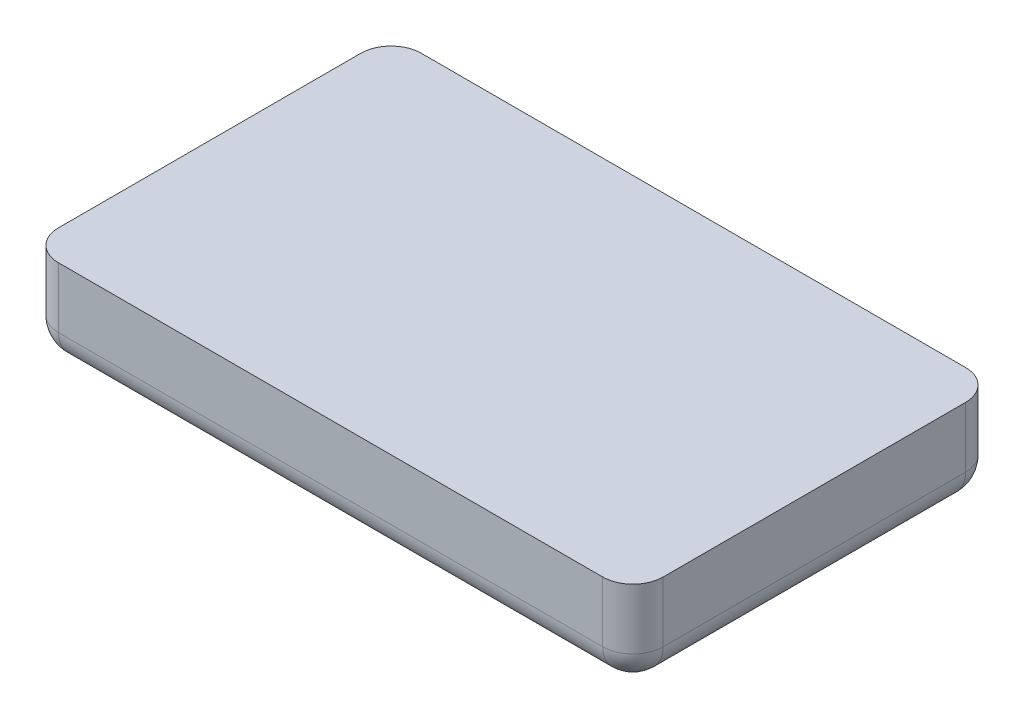
SolidWorks part; units mm, degrees
ref_plane "Front Plane" through (0, 0, 0) normal (0, 0, 1) x (1, 0, 0)
ref_plane "Top Plane" through (0, 0, 0) normal (0, 1, 0) x (1, 0, 0)
ref_plane "Right Plane" through (0, 0, 0) normal (1, 0, 0) x (0, 0, -1)
sketch "Sketch1" plane through (0, 0, 0) normal (0, 1, 0) x (1, 0, 0)
  line L1 (0, 0) -> (200, 0)
  line L2 (0, 0) -> (0, 120)
  line L3 (0, 120) -> (200, 120)
  line L4 (200, 0) -> (200, 120)
  dimension "D1" = 120
  dimension "D2" = 200
extrude "Boss-Extrude1" add sketch "Sketch1" along normal blind 30
fillet "Fillet1" radius 10 8 edges at (0, 15, 0) (200, 0, -60) (0, 0, -60) (100, 0, -120) (100, 0, 0) (200, 15, -120) (200, 15, 0) (0, 15, -120)
sketch "Sketch2" plane through (0, 30, 0) normal (0, 1, 0) x (1, 0, 0)
  line L0 (0, 60) -> (200, 60) construction
  line L1 (0, 110) -> (0, 10) construction
  line L2 (200, 10) -> (200, 110) construction
  line L3 (100, 120) -> (100, 0) construction
  line L4 (10, 0) -> (190, 0) construction
  point P11 (100, 60)
